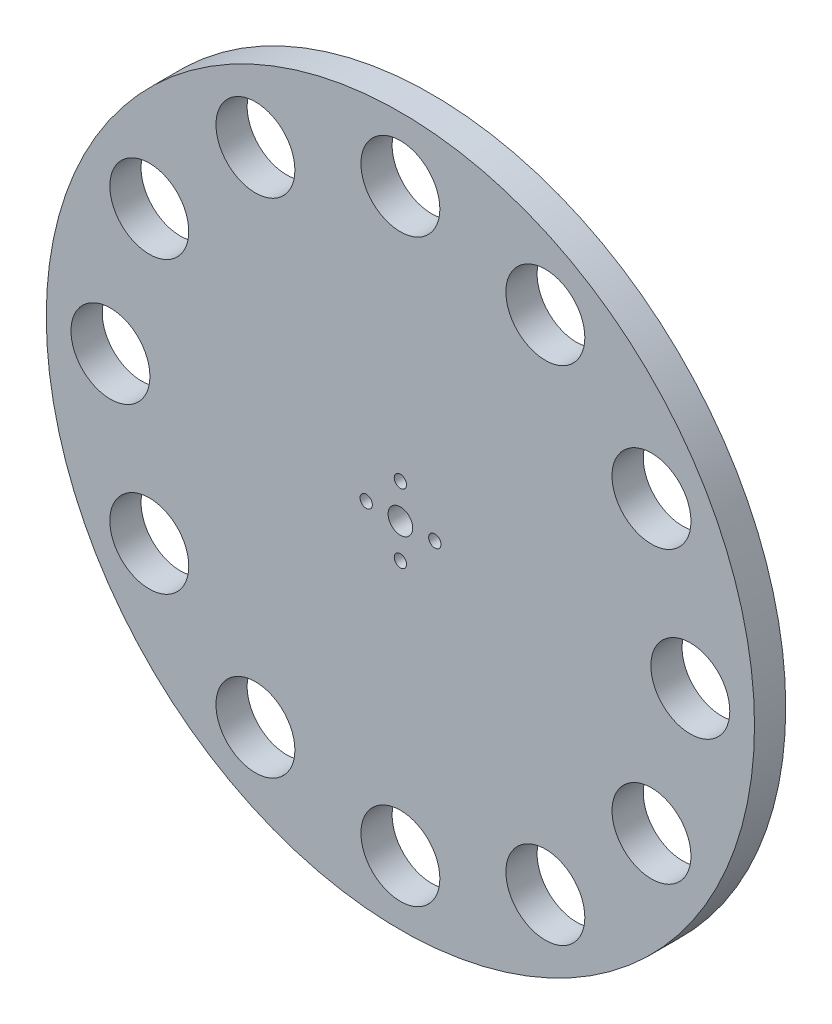
SolidWorks part; units mm, degrees
ref_plane "Front Plane" through (0, 0, 0) normal (0, 0, 1) x (1, 0, 0)
ref_plane "Top Plane" through (0, 0, 0) normal (0, 1, 0) x (1, 0, 0)
ref_plane "Right Plane" through (0, 0, 0) normal (1, 0, 0) x (0, 0, -1)
sketch "Sketch1" plane through (0, 0, 0) normal (0, 0, 1) x (1, 0, 0)
  line L4 (49.7494, 5) -> (50, 5)
  line L12 (-50, -5) -> (-49.7494, -5)
  line L14 (-50, 5) -> (-49.7494, 5)
  line L15 (49.7494, -5) -> (50, -5)
  circle A36 centre (58.95, 0) radius 8.025
  circle A37 centre (51.0522, 29.475) radius 8.025
  circle A38 centre (29.475, 51.0522) radius 8.025
  circle A39 centre (0, 58.95) radius 8.025
  circle A40 centre (-29.475, 51.0522) radius 8.025
  circle A41 centre (-51.0522, 29.475) radius 8.025
  circle A42 centre (-58.95, 0) radius 8.025
  circle A43 centre (-51.0522, -29.475) radius 8.025
  circle A44 centre (-29.475, -51.0522) radius 8.025
  circle A45 centre (0, -58.95) radius 8.025
  circle A46 centre (29.475, -51.0522) radius 8.025
  circle A47 centre (51.0522, -29.475) radius 8.025
  circle A48 centre (0, 0) radius 72
extrude "Boss-Extrude1" add sketch "Sketch1" along normal blind 6.35
sketch "Sketch2" plane through (0, 0, 6.35) normal (0, 0, 1) x (1, 0, 0)
  circle A0 centre (0, 0) radius 2.5
extrude "Cut-Extrude1" cut sketch "Sketch2" against normal blind 10
sketch "Sketch3" plane through (0, 0, 6.35) normal (0, 0, 1) x (1, 0, 0)
  line L0 (0, 0) -> (0, 7)
  line L1 (0, 7) -> (0, 0)
  line L2 (0, 0) -> (7, 0)
  line L3 (7, 0) -> (0, 0)
  line L4 (0, 0) -> (-7, 0)
  line L5 (0, 0) -> (0, -7)
hole_wizard "M3x0.5 Tapped Hole1" positions "3DSketch1" profile "Sketch4" tap size "M3x0.5" standard "ANSI Metric" end condition through all
sketch3d "3DSketch1"
  line L0 (0, 0, 6.35) -> (-7, 0, 6.35) construction
  point P0 (-6.947, 0, 6.35)
sketch "Sketch4" plane through (-6.947, 0, 6.35) normal (1, 0, 0) x (0, -1, 0)
  line L0 (0, 0) -> (0, 6.35)
  line L1 (0, 6.35) -> (1.25, 6.35)
  line L2 (1.25, 6.35) -> (1.25, 0)
  line L5 (1.25, 0) -> (0, 0)
  line L11 (0, -6.35) -> (0, 107.95) construction
  dimension "Thru Tap Drill Dia." = 2.5
  dimension "Thru Tap Drill Depth" = 6.35
cosmetic thread "Hole Thread1" parameters "D2"=3
hole_wizard "M3x0.5 Tapped Hole2" positions "3DSketch2" profile "Sketch5" tap size "M3x0.5" standard "ANSI Metric" end condition through all
sketch3d "3DSketch2"
  point P0 (0, 7, 6.35)
sketch "Sketch5" plane through (0, 7, 6.35) normal (1, 0, 0) x (0, -1, 0)
  line L0 (0, 0) -> (0, 6.35)
  line L1 (0, 6.35) -> (1.25, 6.35)
  line L2 (1.25, 6.35) -> (1.25, 0)
  line L5 (1.25, 0) -> (0, 0)
  line L11 (0, -6.35) -> (0, 107.95) construction
  dimension "Thru Tap Drill Dia." = 2.5
  dimension "Thru Tap Drill Depth" = 6.35
cosmetic thread "Hole Thread2" parameters "D2"=3
hole_wizard "M3x0.5 Tapped Hole3" positions "3DSketch3" profile "Sketch6" tap size "M3x0.5" standard "ANSI Metric" end condition through all
sketch3d "3DSketch3"
  point P0 (0, -7, 6.35)
sketch "Sketch6" plane through (0, -7, 6.35) normal (1, 0, 0) x (0, -1, 0)
  line L0 (0, 0) -> (0, 6.35)
  line L1 (0, 6.35) -> (1.25, 6.35)
  line L2 (1.25, 6.35) -> (1.25, 0)
  line L5 (1.25, 0) -> (0, 0)
  line L11 (0, -6.35) -> (0, 107.95) construction
  dimension "Thru Tap Drill Dia." = 2.5
  dimension "Thru Tap Drill Depth" = 6.35
cosmetic thread "Hole Thread3" parameters "D2"=3
hole_wizard "M3x0.5 Tapped Hole4" positions "3DSketch4" profile "Sketch7" tap size "M3x0.5" standard "ANSI Metric" end condition through all
sketch3d "3DSketch4"
  point P0 (7, 0, 6.35)
sketch "Sketch7" plane through (7, 0, 6.35) normal (1, 0, 0) x (0, -1, 0)
  line L0 (0, 0) -> (0, 6.35)
  line L1 (0, 6.35) -> (1.25, 6.35)
  line L2 (1.25, 6.35) -> (1.25, 0)
  line L5 (1.25, 0) -> (0, 0)
  line L11 (0, -6.35) -> (0, 107.95) construction
  dimension "Thru Tap Drill Dia." = 2.5
  dimension "Thru Tap Drill Depth" = 6.35
cosmetic thread "Hole Thread4" parameters "D2"=3
